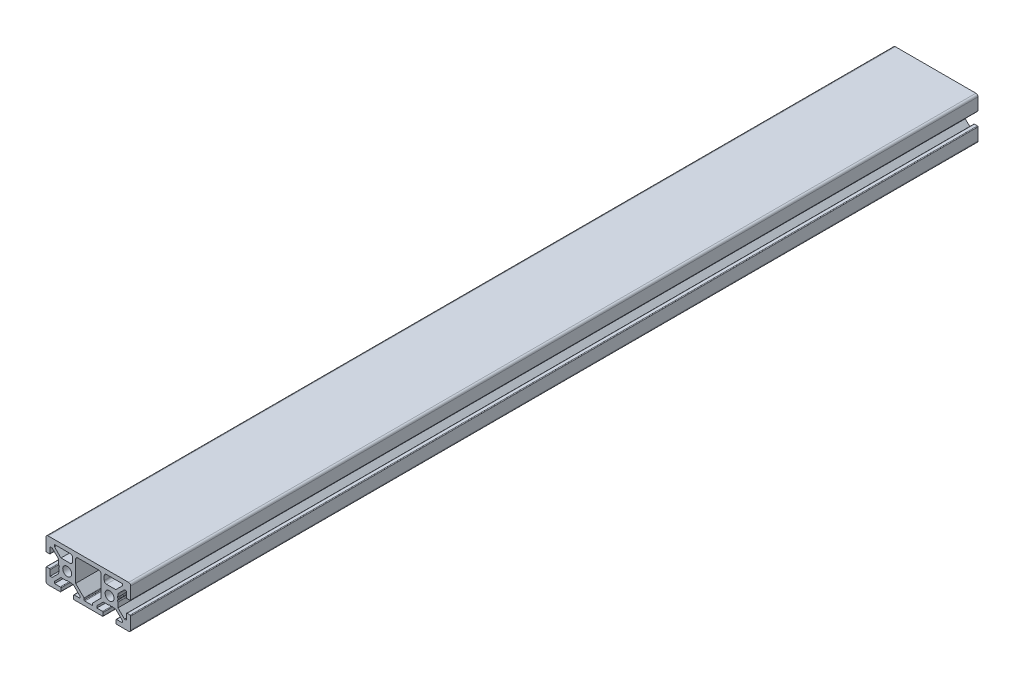
SolidWorks part; units mm, degrees
material "1060 Alloy"
ref_plane "Front Plane" through (0, 0, 0) normal (0, 0, 1) x (1, 0, 0)
ref_plane "Top Plane" through (0, 0, 0) normal (0, 1, 0) x (1, 0, 0)
ref_plane "Right Plane" through (0, 0, 0) normal (1, 0, 0) x (0, 0, -1)
sketch "Model" plane through (0, 0, 0) normal (0, 0, 1) x (1, 0, 0)
  line L0 (-10, 6) -> (-10, -6) construction
  line L1 (22, 0) -> (-22, 0) construction
  line L2 (19, 10) -> (-19, 10)
  line L3 (6.7, -10) -> (-6.7, -10)
  line L4 (20, 9) -> (20, 3.3)
  line L5 (-20, 9) -> (-20, 3.3)
  line L6 (-14, 2.9393) -> (-14, 0.6536)
  line L7 (-8.5, 4) -> (-12.9393, 4)
  line L8 (-8.5, 8) -> (-16, 8)
  line L9 (-18, 6) -> (-18, 3.3)
  line L10 (-18.3, 3) -> (-19.7, 3)
  line L11 (-18.3, -3) -> (-19.7, -3)
  line L12 (-17.0607, -6) -> (-18, -6)
  line L13 (-18, -3.3) -> (-18, -6)
  line L14 (-20, -3.3) -> (-20, -9)
  line L15 (-17.0607, 6) -> (-18, 6)
  line L16 (-13.933, -0.4036) -> (-13.7, 0)
  line L17 (-13.933, 0.4036) -> (-13.7, 0)
  line L18 (-14, -2.5) -> (-14, -2.9393)
  line L19 (-14, 2.9393) -> (-17.0607, 6)
  line L20 (-14, -2.9393) -> (-17.0607, -6)
  line L21 (-14, -2.5) -> (-13.751, -1.2189)
  line L22 (-13.933, -0.9036) -> (-13.751, -1.2189)
  line L23 (-12.9393, -4) -> (-10.6536, -4)
  line L24 (-7.5, -4) -> (-7.0607, -4)
  line L25 (-16, -8) -> (-13.3, -8)
  line L26 (-6.7, -8) -> (-4, -8)
  line L27 (-4, -7.0607) -> (-4, -8)
  line L28 (-16, -7.0607) -> (-16, -8)
  line L29 (-7, -8.3) -> (-7, -9.7)
  line L30 (-13, -8.3) -> (-13, -9.7)
  line L31 (-9.5964, -3.933) -> (-10, -3.7)
  line L32 (-10.4036, -3.933) -> (-10, -3.7)
  line L33 (-7.0607, -4) -> (-4, -7.0607)
  line L34 (-12.9393, -4) -> (-16, -7.0607)
  line L35 (-7.5, -4) -> (-8.7811, -3.751)
  line L36 (-9.0964, -3.933) -> (-8.7811, -3.751)
  line L37 (-13.3, -10) -> (-19, -10)
  line L38 (-12.9393, 4) -> (-16, 7.0607)
  line L39 (-16, 8) -> (-16, 7.0607)
  line L45 (14, -2.9393) -> (14, -0.6536)
  line L46 (14, 2.5) -> (14, 2.9393)
  line L47 (18, -6) -> (18, -3.3)
  line L48 (18, 3.3) -> (18, 6)
  line L49 (17.0607, 6) -> (18, 6)
  line L50 (17.0607, -6) -> (18, -6)
  line L51 (18.3, 3) -> (19.7, 3)
  line L52 (18.3, -3) -> (19.7, -3)
  line L53 (13.933, 0.4036) -> (13.7, 0)
  line L54 (13.933, -0.4036) -> (13.7, 0)
  line L55 (14, 2.9393) -> (17.0607, 6)
  line L56 (14, -2.9393) -> (17.0607, -6)
  line L57 (14, 2.5) -> (13.751, 1.2189)
  line L58 (13.933, 0.9036) -> (13.751, 1.2189)
  line L59 (20, -3.3) -> (20, -9)
  line L65 (0, 12) -> (0, -12) construction
  line L66 (10, 6) -> (10, -6) construction
  line L67 (7.0607, -4) -> (9.3464, -4)
  line L68 (12.5, -4) -> (12.9393, -4)
  line L69 (4, -8) -> (6.7, -8)
  line L70 (13.3, -8) -> (16, -8)
  line L71 (16, -7.0607) -> (16, -8)
  line L72 (4, -7.0607) -> (4, -8)
  line L73 (13, -8.3) -> (13, -9.7)
  line L74 (7, -8.3) -> (7, -9.7)
  line L75 (10.4036, -3.933) -> (10, -3.7)
  line L76 (9.5964, -3.933) -> (10, -3.7)
  line L77 (12.9393, -4) -> (16, -7.0607)
  line L78 (7.0607, -4) -> (4, -7.0607)
  line L79 (12.5, -4) -> (11.2189, -3.751)
  line L80 (10.9036, -3.933) -> (11.2189, -3.751)
  line L81 (13.3, -10) -> (19, -10)
  line L82 (8.5, 4) -> (12.9393, 4)
  line L83 (8.5, 8) -> (16, 8)
  line L84 (12.9393, 4) -> (16, 7.0607)
  line L85 (16, 8) -> (16, 7.0607)
  line L86 (-7.5, 7) -> (-7.5, 5)
  line L87 (7.5, 7) -> (7.5, 5)
  line L88 (-6, 7) -> (-6, -2.9393)
  line L89 (6, 7) -> (6, -2.9393)
  line L90 (-6, -2.9393) -> (-2.0879, -6.8515)
  line L91 (6, -2.9393) -> (2.0879, -6.8515)
  line L92 (-5, 8) -> (5, 8)
  line L93 (2, -7.0636) -> (2, -7.7)
  line L94 (-2, -7.0636) -> (-2, -7.7)
  line L95 (-1.7, -8) -> (1.7, -8)
  arc A0 (-13.933, -0.4036) -> (-13.933, -0.9036) centre (-13.5, -0.6536) ccw
  arc A1 (-14, 0.6536) -> (-13.933, 0.4036) centre (-13.5, 0.6536) ccw
  arc A2 (-18.3, 3) -> (-18, 3.3) centre (-18.3, 3.3) ccw
  arc A3 (-20, 3.3) -> (-19.7, 3) centre (-19.7, 3.3) ccw
  arc A4 (-18, -3.3) -> (-18.3, -3) centre (-18.3, -3.3) ccw
  arc A5 (-19.7, -3) -> (-20, -3.3) centre (-19.7, -3.3) ccw
  arc A6 (-13.3, -10) -> (-13, -9.7) centre (-13.3, -9.7) ccw
  arc A7 (-13, -8.3) -> (-13.3, -8) centre (-13.3, -8.3) ccw
  arc A8 (-6.7, -8) -> (-7, -8.3) centre (-6.7, -8.3) ccw
  arc A9 (-7, -9.7) -> (-6.7, -10) centre (-6.7, -9.7) ccw
  arc A10 (-10.6536, -4) -> (-10.4036, -3.933) centre (-10.6536, -3.5) ccw
  arc A11 (-9.5964, -3.933) -> (-9.0964, -3.933) centre (-9.3464, -3.5) ccw
  circle A12 centre (-10, 0) radius 2.1
  arc A13 (20, 9) -> (19, 10) centre (19, 9) ccw
  arc A14 (19, -10) -> (20, -9) centre (19, -9) ccw
  arc A15 (-20, -9) -> (-19, -10) centre (-19, -9) ccw
  arc A16 (-19, 10) -> (-20, 9) centre (-19, 9) ccw
  arc A17 (20, -3.3) -> (19.7, -3) centre (19.7, -3.3) ccw
  arc A18 (18.3, -3) -> (18, -3.3) centre (18.3, -3.3) ccw
  arc A19 (18, 3.3) -> (18.3, 3) centre (18.3, 3.3) ccw
  arc A20 (19.7, 3) -> (20, 3.3) centre (19.7, 3.3) ccw
  arc A21 (14, -0.6536) -> (13.933, -0.4036) centre (13.5, -0.6536) ccw
  arc A22 (13.933, 0.4036) -> (13.933, 0.9036) centre (13.5, 0.6536) ccw
  arc A23 (6.7, -10) -> (7, -9.7) centre (6.7, -9.7) ccw
  arc A24 (7, -8.3) -> (6.7, -8) centre (6.7, -8.3) ccw
  arc A25 (13.3, -8) -> (13, -8.3) centre (13.3, -8.3) ccw
  arc A26 (13, -9.7) -> (13.3, -10) centre (13.3, -9.7) ccw
  arc A27 (9.3464, -4) -> (9.5964, -3.933) centre (9.3464, -3.5) ccw
  arc A28 (10.4036, -3.933) -> (10.9036, -3.933) centre (10.6536, -3.5) ccw
  circle A29 centre (10, 0) radius 2.1
  arc A30 (7.5, 5) -> (8.5, 4) centre (8.5, 5) ccw
  arc A31 (8.5, 8) -> (7.5, 7) centre (8.5, 7) ccw
  arc A32 (6, 7) -> (5, 8) centre (5, 7) ccw
  arc A33 (-5, 8) -> (-6, 7) centre (-5, 7) ccw
  arc A34 (-7.5, 7) -> (-8.5, 8) centre (-8.5, 7) ccw
  arc A35 (-8.5, 4) -> (-7.5, 5) centre (-8.5, 5) ccw
  arc A36 (-2, -7.0636) -> (-2.0879, -6.8515) centre (-2.3, -7.0636) ccw
  arc A37 (-2, -7.7) -> (-1.7, -8) centre (-1.7, -7.7) ccw
  arc A38 (2.0879, -6.8515) -> (2, -7.0636) centre (2.3, -7.0636) ccw
  arc A39 (1.7, -8) -> (2, -7.7) centre (1.7, -7.7) ccw
extrude "Boss-Extrude1" add sketch "Model" along normal blind 400
